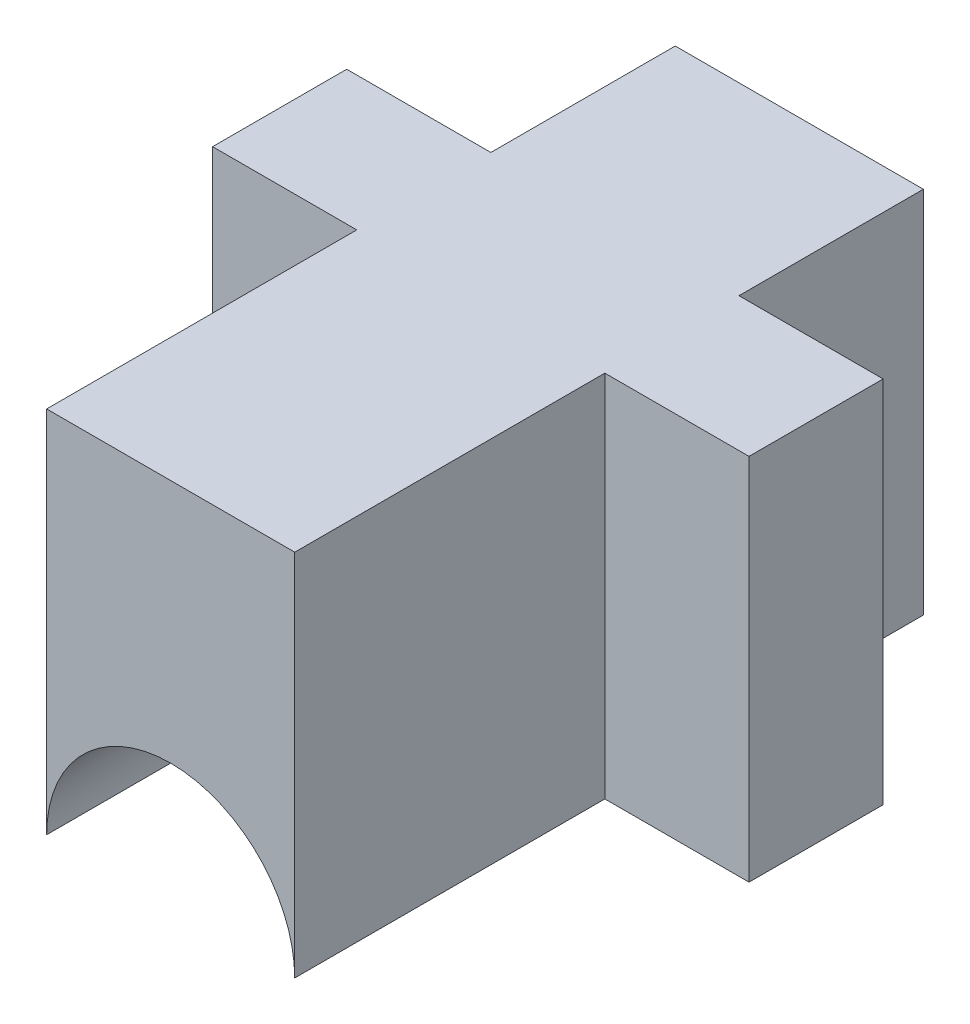
SolidWorks part; units mm, degrees
ref_plane "Plan de face" through (0, 0, 0) normal (0, 0, 1) x (1, 0, 0)
ref_plane "Plan de dessus" through (0, 0, 0) normal (0, 1, 0) x (1, 0, 0)
ref_plane "Plan de droite" through (0, 0, 0) normal (1, 0, 0) x (0, 0, -1)
sketch "Esquisse1" plane through (0, 0, 0) normal (0, 1, 0) x (1, 0, 0)
  line L0 (-17.3744, 37.1595) -> (-9.9744, 37.1595)
  line L1 (-17.3744, 37.1595) -> (-17.3744, 32.1595)
  line L2 (-9.9744, 37.1595) -> (-9.9744, 32.1595)
  line L3 (-9.9744, 32.1595) -> (-5.6744, 32.1595)
  line L4 (-17.3744, 32.1595) -> (-21.6744, 32.1595)
  line L5 (-21.6744, 32.1595) -> (-21.6744, 27.1595)
  line L6 (-5.6744, 32.1595) -> (-5.6744, 27.1595)
  line L7 (-5.6744, 27.1595) -> (-9.9744, 27.1595)
  line L8 (-21.6744, 27.1595) -> (-17.3744, 27.1595)
  line L9 (-17.3744, 27.1595) -> (-17.3744, 18.4095)
  line L10 (-17.3744, 18.4095) -> (-9.9744, 18.4095)
  line L11 (-9.9744, 27.1595) -> (-9.9744, 18.4095)
extrude "Boss.-Extru.1" add sketch "Esquisse1" along normal blind 11 contours L11 L10 L9 L8 L5 L4 L1 L0 L2 L3 L6 L7
sketch "Esquisse2" plane through (0, 0, -18.4095) normal (0, 0, 1) x (1, 0, 0)
  line L0 (-17.3744, 0) -> (-9.9744, 0)
  circle A0 centre (-13.6744, 0) radius 3.7
  line M1 (-17.3744, 0) -> (-9.9744, 0)
extrude "Enlèv. mat.-Extru.1" cut sketch "Esquisse2" against normal through all contours A0 M1
sketch "Esquisse3" plane through (0, 11, 0) normal (0, 1, 0) x (1, 0, 0)
  line L0 (-5.6744, 32.1595) -> (-5.6744, 31.6595)
  line L1 (-5.6744, 32.1595) -> (-5.6744, 27.1595) construction
  line L2 (-9.9744, 32.1595) -> (-9.9744, 31.6595)
  line L3 (-9.9744, 31.6595) -> (-5.6744, 31.6595)
  line L4 (-9.9744, 32.1595) -> (-5.6744, 32.1595)
  line L5 (-17.3744, 32.1595) -> (-17.3744, 31.6595)
  line L6 (-17.3744, 31.6595) -> (-21.6744, 31.6595)
  line L7 (-21.6744, 32.1595) -> (-21.6744, 27.1595) construction
  line L8 (-21.6744, 31.6595) -> (-21.6744, 32.1595)
  line L9 (-21.6744, 32.1595) -> (-17.3744, 32.1595)
  line L10 (-21.6744, 27.1595) -> (-21.6744, 27.6595)
  line L11 (-21.6744, 27.6595) -> (-17.3744, 27.6595)
  line L12 (-17.3744, 27.6595) -> (-17.3744, 27.1595)
  line L13 (-17.3744, 27.1595) -> (-21.6744, 27.1595)
  line L14 (-9.9744, 27.1595) -> (-5.6744, 27.1595)
  line L15 (-5.6744, 27.1595) -> (-9.9744, 27.1595) construction
  line L16 (-5.6744, 27.1595) -> (-5.6744, 27.6595)
  line L17 (-5.6744, 27.6595) -> (-9.9744, 27.6595)
  line L18 (-9.9744, 27.6595) -> (-9.9744, 27.1595)
extrude "Enlèv. mat.-Extru.2" cut sketch "Esquisse3" against normal through all contours L9 L5 L6 L8 | L13 L10 L11 L12 | L18 L14 L16 L17 | L4 L0 L3 L2
